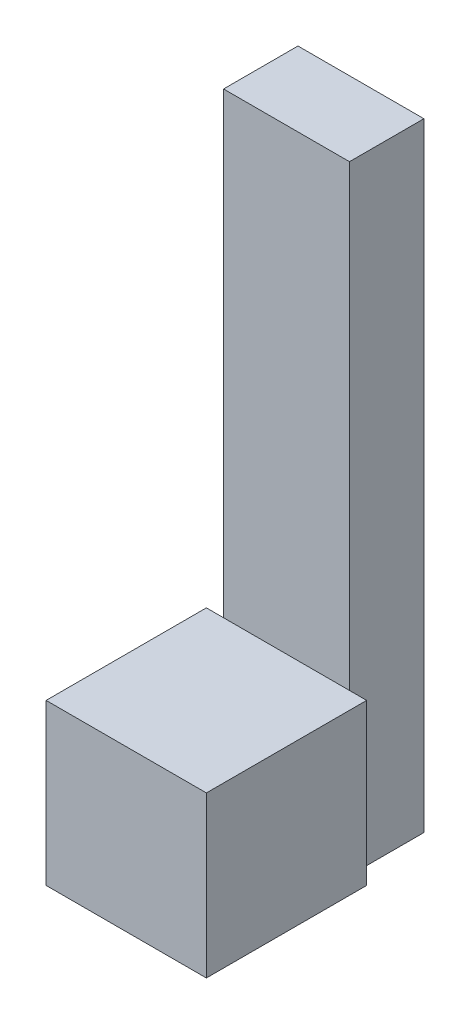
SolidWorks part; units mm, degrees
ref_plane "Front Plane" through (0, 0, 0) normal (0, 0, 1) x (1, 0, 0)
ref_plane "Top Plane" through (0, 0, 0) normal (0, 1, 0) x (1, 0, 0)
ref_plane "Right Plane" through (0, 0, 0) normal (1, 0, 0) x (0, 0, -1)
sketch "Sketch1" plane through (0, 0, 0) normal (0, 0, 1) x (1, 0, 0)
  line L1 (-5.5, 27) -> (5.5, 27)
  line L2 (-5.5, 27) -> (-5.5, -27)
  line L3 (-5.5, -27) -> (5.5, -27)
  line L4 (5.5, 27) -> (5.5, -27)
  line L5 (-5.5, 27) -> (5.5, -27) construction
  line L6 (-5.5, -27) -> (5.5, 27) construction
  point P0 (0, 0)
  dimension "D1" = 54
  dimension "D2" = 11
extrude "Boss-Extrude1" add sketch "Sketch1" along normal mid plane 6.5
sketch "Sketch2" plane through (0, 0, 3.25) normal (0, 0, 1) x (1, 0, 0)
  line L0 (0, 27) -> (0, -27) construction
  line L1 (-7, -13) -> (7, -13)
  line L2 (-7, -13) -> (-7, -27)
  line L3 (-7, -27) -> (7, -27)
  line L4 (7, -13) -> (7, -27)
  line L5 (-7, -13) -> (7, -27) construction
  line L6 (-7, -27) -> (7, -13) construction
  line L7 (5.5, 27) -> (-5.5, 27) construction
  line L8 (-5.5, -27) -> (5.5, -27) construction
  point P0 (0, -20)
  dimension "D1" = 14
  dimension "D2" = 14
extrude "Boss-Extrude3" add sketch "Sketch2" along normal blind 14
